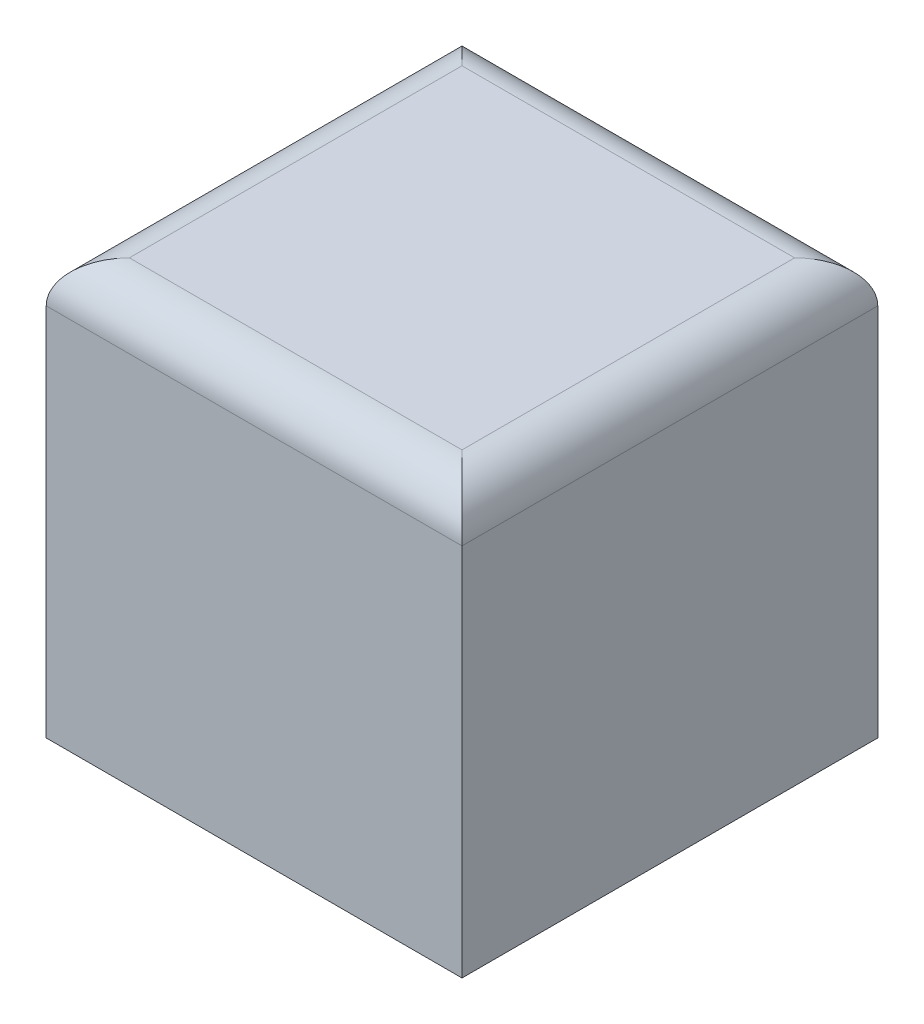
SolidWorks part; units mm, degrees
ref_plane "前视基准面" through (0, 0, 0) normal (0, 0, 1) x (1, 0, 0)
ref_plane "上视基准面" through (0, 0, 0) normal (0, 1, 0) x (1, 0, 0)
ref_plane "右视基准面" through (0, 0, 0) normal (1, 0, 0) x (0, 0, -1)
other "Configuration Table"
sketch "草图1" plane through (0, 0, 0) normal (0, 0, 1) x (1, 0, 0)
  line L1 (-50, -50) -> (50, -50)
  line L2 (-50, -50) -> (-50, 50)
  line L3 (-50, 50) -> (50, 50)
  line L4 (50, -50) -> (50, 50)
  line L5 (-50, -50) -> (50, 50) construction
  line L6 (-50, 50) -> (50, -50) construction
  point P0 (0, 0)
extrude "凸台-拉伸1" add sketch "草图1" along normal blind 100
fillet "圆角1" radius 10 4 edges at (0, 50, 0) (-50, 50, 50) (50, 50, 50) (0, 50, 100)
